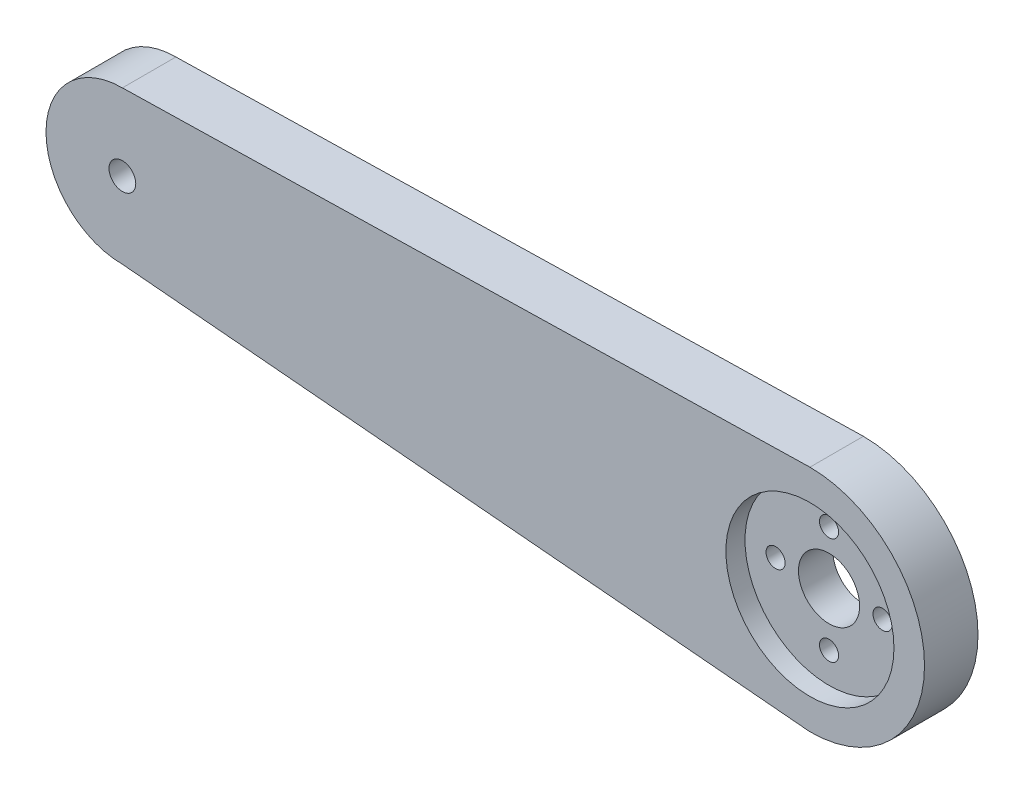
SolidWorks part; units mm, degrees
ref_plane "前视基准面" through (0, 0, 0) normal (0, 0, 1) x (1, 0, 0)
ref_plane "上视基准面" through (0, 0, 0) normal (0, 1, 0) x (1, 0, 0)
ref_plane "右视基准面" through (0, 0, 0) normal (1, 0, 0) x (0, 0, -1)
sketch "草图1" plane through (0, 0, 0) normal (0, 0, 1) x (1, 0, 0)
  line L0 (0, -10) -> (90, -18)
  line L3 (0, 10) -> (90, 12)
  arc A2 (90, -18) -> (90, 12) centre (90, -3) ccw
  arc A3 (0, 10) -> (0, -10) centre (0, 0) ccw
extrude "凸台-拉伸1" add sketch "草图1" along normal blind 7
sketch "草图2" plane through (0, 0, 0) normal (0, 0, -1) x (-1, 0, 0)
  circle A1 centre (0, 0) radius 4.1
  circle A2 centre (-90, -10) radius 1.25
  circle A3 centre (-83, -3) radius 1.25
  circle A4 centre (-90, 4) radius 1.25
  circle A5 centre (-97, -3) radius 1.25
  circle A6 centre (-90, -3) radius 4
  arc A8 (-90, 12) -> (-90, -18) centre (-90, -3) ccw construction
  point P17 (-90, -3)
  dimension "D1" = 4
  dimension "D2" = 7
  dimension "D3" = 2.5
extrude "切除-拉伸1" cut sketch "草图2" against normal blind 10
sketch "草图3" plane through (0, 0, 7) normal (0, 0, 1) x (1, 0, 0)
  circle A0 centre (90, -3) radius 11
extrude "切除-拉伸2" cut sketch "草图3" against normal blind 2.5
sketch "草图7" plane through (0, 0, 0) normal (0, 0, -1) x (-1, 0, 0)
  circle A0 centre (0, 0) radius 4.1
extrude "凸台-拉伸4" add sketch "草图7" against normal blind 7
sketch "草图13" plane through (0, 0, 7) normal (0, 0, 1) x (1, 0, 0)
  circle A0 centre (0, 0) radius 1.75
extrude "切除-拉伸3" cut sketch "草图13" against normal blind 10
sketch "草图15" plane through (0, 0, 0) normal (0, 0, -1) x (-1, 0, 0)
  circle A0 centre (0, 0) radius 4.01
extrude "切除-拉伸5" cut sketch "草图15" against normal blind 3
